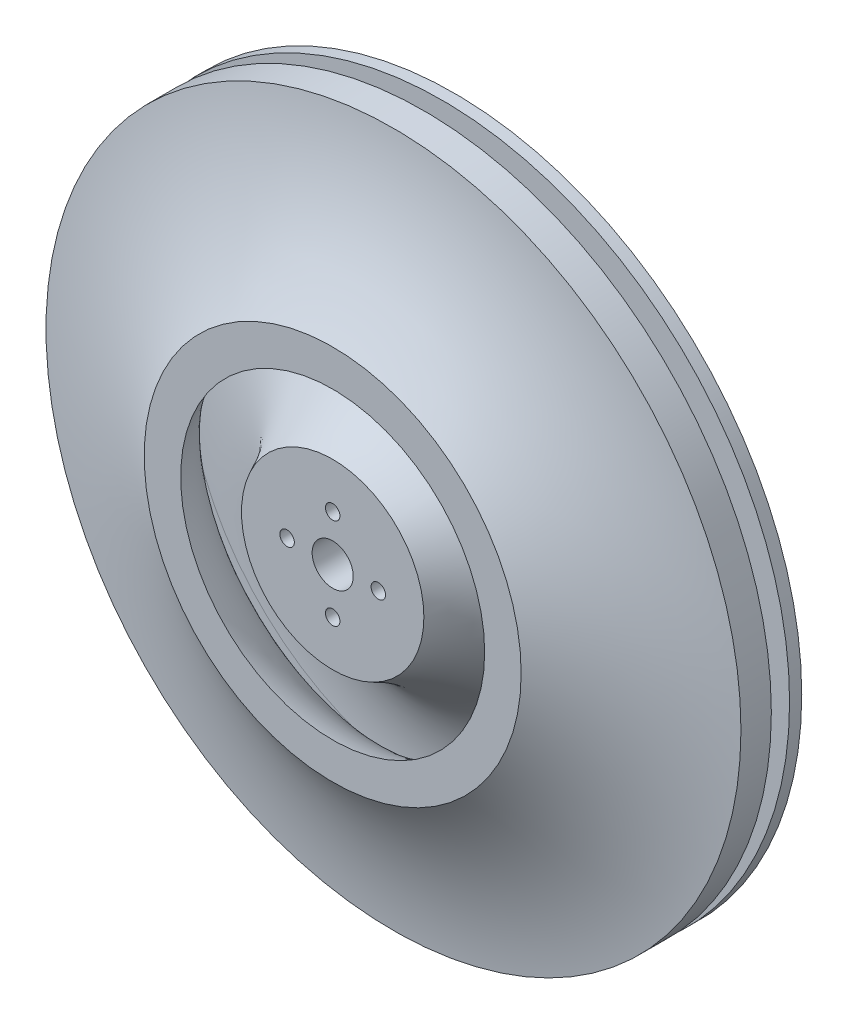
SolidWorks part; units mm, degrees
material "Titanium"
ref_plane "Front Plane" through (0, 0, 0) normal (1, 0, 0) x (0, 1, 0)
ref_plane "Top Plane" through (0, 0, 0) normal (0, 0, 1) x (0, 1, 0)
ref_plane "Right Plane" through (0, 0, 0) normal (0, 1, 0) x (-1, 0, 0)
sketch "Sketch1" plane through (0, 0, 0) normal (1, 0, 0) x (0, 1, 0)
  line L0 (-15, 20) -> (0, 20)
  line L1 (0, 20) -> (0, 5)
  line L2 (0, 5) -> (-15, 5)
  line L3 (-15, 5) -> (-15, 0)
  line L5 (-25.275, 0) -> (-25.275, 1)
  line L6 (-25.275, 1) -> (-27.525, 1)
  line L7 (-27.525, 1) -> (-27.525, 0)
  line L8 (-27.525, 0) -> (-29.275, 0)
  line L9 (-29.275, 0) -> (-29.275, 1)
  line L10 (-29.275, 1) -> (-31.525, 1)
  line L11 (-31.525, 1) -> (-31.525, 0)
  line L12 (-31.525, 0) -> (-33.275, 0)
  line L13 (-33.275, 0) -> (-33.275, 1)
  line L14 (-33.275, 1) -> (-35.525, 1)
  line L15 (-35.525, 1) -> (-35.525, 0)
  line L16 (-35.525, 0) -> (-37.275, 0)
  line L17 (-37.275, 0) -> (-37.275, 1)
  line L18 (-37.275, 1) -> (-39.525, 1)
  line L19 (-39.525, 1) -> (-39.525, 0)
  line L20 (-39.525, 0) -> (-57.15, 0)
  line L21 (-57.15, 0) -> (-57.15, 2)
  line L22 (-57.15, 2) -> (-42.15, 2)
  line L23 (-57.15, 5) -> (-42.15, 6.3123)
  line L26 (-57.15, 10) -> (-57.15, 5)
  line L27 (0, 5) -> (0, 0) construction
  line L28 (-25.275, 0) -> (-15, 0)
  line L29 (-31, 20) -> (-25, 20)
  arc A1 (-42.15, 2) -> (-15, 20) centre (-42.15, 31.4756) ccw
  arc A2 (-42.15, 6.3123) -> (-25, 20) centre (-43.8782, 26.0656) ccw
  arc A3 (-57.15, 10) -> (-31, 20) centre (-63.0731, 64.6801) ccw
  point P31 (-26.4, 1)
  point P32 (-30.4, 1)
  point P36 (-24.5825, 1.044)
  point P37 (-27.25, 0.9468)
  point P38 (-27.25, 1.5344)
  point P39 (0, 0)
  dimension "D1" = 57.15
  dimension "D13" = 20
  dimension "D15" = 31
  dimension "D16" = 55
  dimension "D2" = 15
  dimension "D3" = 11.4
  dimension "D4" = 4
  dimension "D5" = 1
  dimension "D6" = 5
  dimension "D7" = 3
  dimension "D8" = 2
  dimension "D9" = 15
  dimension "D10" = 10
  dimension "D11" = 15
  dimension "D12" = 5
  dimension "D14" = 10
  dimension "D17" = 1.75
ref_axis "Axis1" through (0, 0, 21) along (0, 0, -1)
revolve "Revolve1" add sketch "Sketch1" angle 360 about axis through (0, 0, 21) along (0, 0, -1)
sketch "Sketch2" plane through (0, 0, 0) normal (0, 0, 1) x (0, 1, 0)
  line L0 (-7.5, 0) -> (7.5, 0) construction
  line L1 (0, 7.5) -> (0, -7.5) construction
  circle A0 centre (0, 0) radius 3.3782
  circle A1 centre (0, 7.5) radius 1.1906
  circle A2 centre (7.5, 0) radius 1.1906
  circle A3 centre (0, -7.5) radius 1.1906
  circle A4 centre (-7.5, 0) radius 1.1906
  point P11 (-8.269, 0)
  dimension "D1" = 2.3812
  dimension "D2" = 6.7564
  dimension "D3" = 15
extrude "Cut-Extrude1" cut sketch "Sketch2" along normal through all both and the other way through all contours A4 | A1 | A2 | A3 | A0
